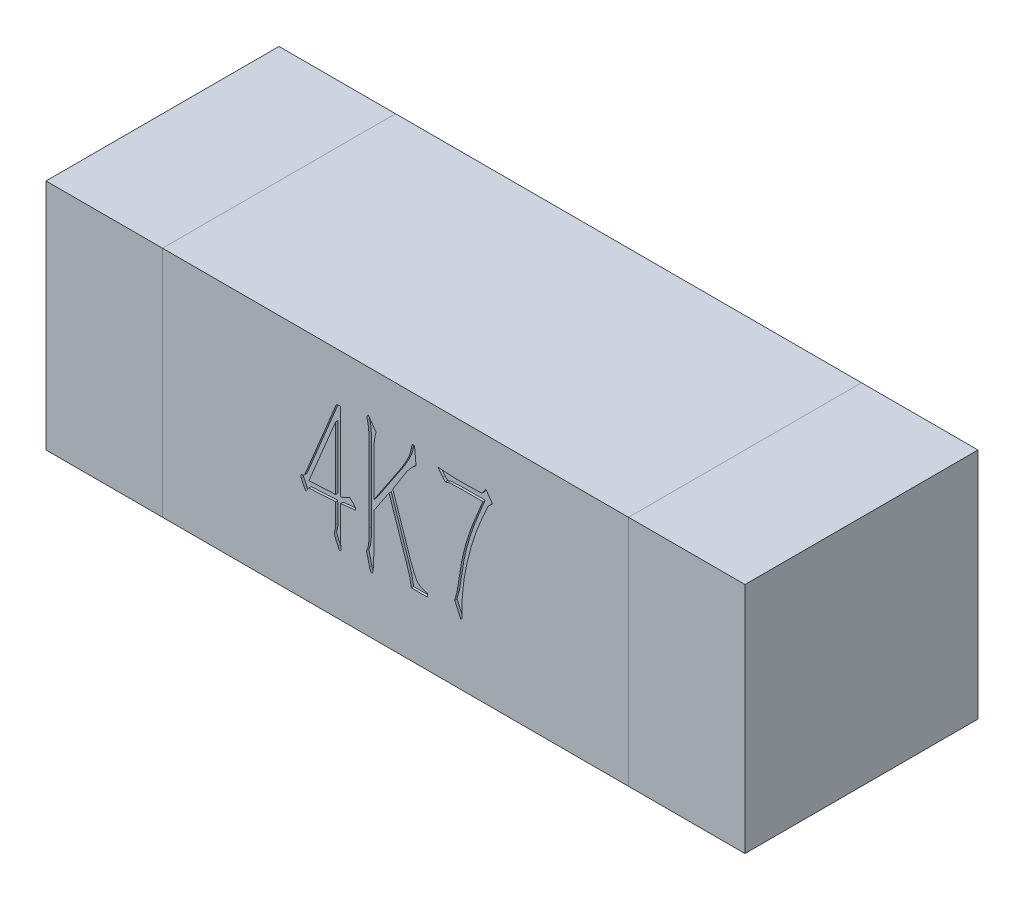
SolidWorks part; units mm, degrees
ref_plane "前视基准面" through (0, 0, 0) normal (0, 0, 1) x (1, 0, 0)
ref_plane "上视基准面" through (0, 0, 0) normal (0, 1, 0) x (1, 0, 0)
ref_plane "右视基准面" through (0, 0, 0) normal (1, 0, 0) x (0, 0, -1)
sketch "草图1" plane through (0, 0, 0) normal (0, 0, 1) x (1, 0, 0)
  line L1 (-1, 0.5) -> (1, 0.5)
  line L2 (-1, 0.5) -> (-1, -0.5)
  line L3 (-1, -0.5) -> (1, -0.5)
  line L4 (1, 0.5) -> (1, -0.5)
  line L5 (-1, 0.5) -> (1, -0.5) construction
  line L6 (-1, -0.5) -> (1, 0.5) construction
  point P0 (0, 0)
extrude "凸台-拉伸1" add sketch "草图1" along normal blind 1
sketch "草图2" plane through (0, 0, 0) normal (0, 0, -1) x (-1, 0, 0)
  line L1 (1, 0.5) -> (1.5, 0.5)
  line L2 (1, 0.5) -> (1, -0.5)
  line L3 (1, -0.5) -> (1.5, -0.5)
  line L4 (1.5, 0.5) -> (1.5, -0.5)
  line L5 (-1, 0.5) -> (-1.5, 0.5)
  line L6 (-1, 0.5) -> (-1, -0.5)
  line L7 (-1, -0.5) -> (-1.5, -0.5)
  line L8 (-1.5, 0.5) -> (-1.5, -0.5)
extrude "凸台-拉伸2" add sketch "草图2" against normal blind 1 separate body
sketch "草图4" plane through (0, 0, 1) normal (0, 0, 1) x (1, 0, 0)
  line L0 (-0.4333, -0.2761) -> (0.6895, -0.2761) construction
  text T0 "4K7" font "汉仪长仿宋体" height in points 2
extrude "切除-拉伸1" cut sketch "草图4" against normal blind 0.01
